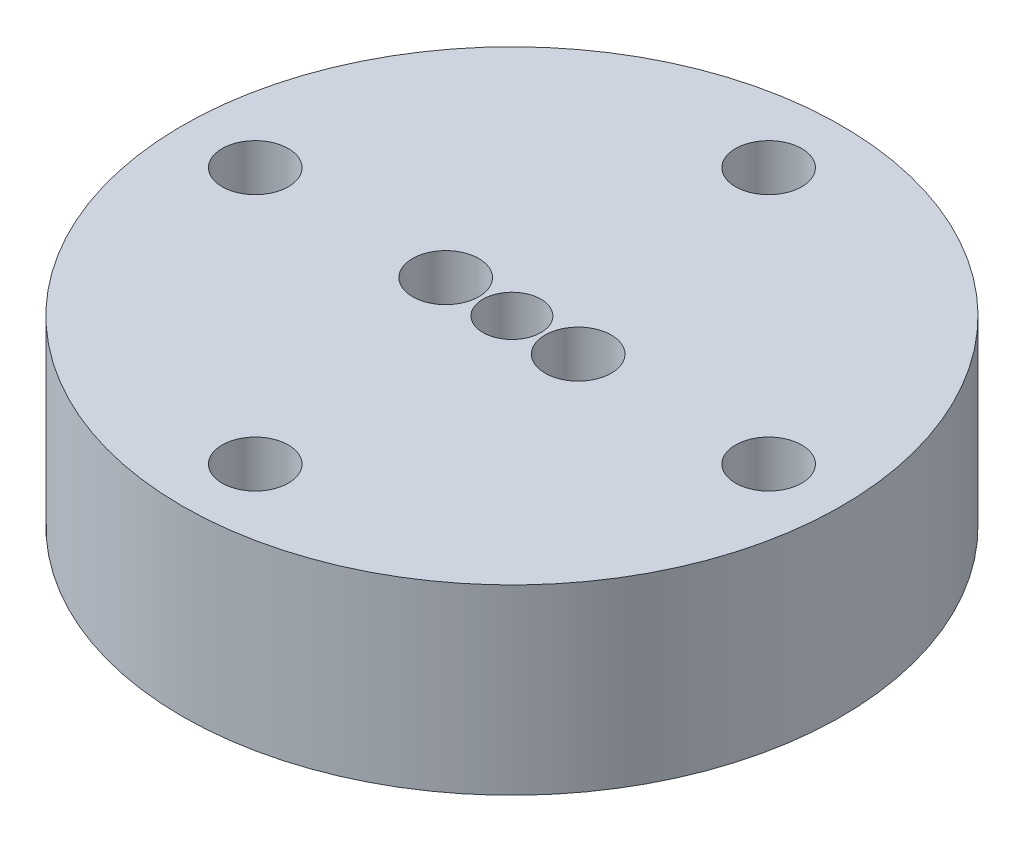
SolidWorks part; units mm, degrees
ref_plane "Front Plane" through (0, 0, 0) normal (0, 0, 1) x (1, 0, 0)
ref_plane "Top Plane" through (0, 0, 0) normal (0, 1, 0) x (1, 0, 0)
ref_plane "Right Plane" through (0, 0, 0) normal (1, 0, 0) x (0, 0, -1)
sketch "Sketch1" plane through (0, 0, 0) normal (0, 1, 0) x (1, 0, 0)
  circle A0 centre (0, 0) radius 15.5 construction
  circle A1 centre (0, 15.5) radius 2
  circle A2 centre (15.5, 0) radius 2
  circle A3 centre (0, -15.5) radius 2
  circle A4 centre (-15.5, 0) radius 2
  circle A5 centre (0, 0) radius 19.9
  circle A6 centre (0, 0) radius 4 construction
  circle A7 centre (-4, 0) radius 2
  circle A8 centre (4, 0) radius 2
  circle A9 centre (0, 0) radius 1.75
  point P14 (0, 0)
  dimension "D1" = 31
  dimension "D2" = 4
  dimension "D4" = 39.8
  dimension "D5" = 8
  dimension "D6" = 4
  dimension "D7" = 3.5
  dimension "D3" = 4
extrude "Boss-Extrude1" add sketch "Sketch1" along normal blind 11
